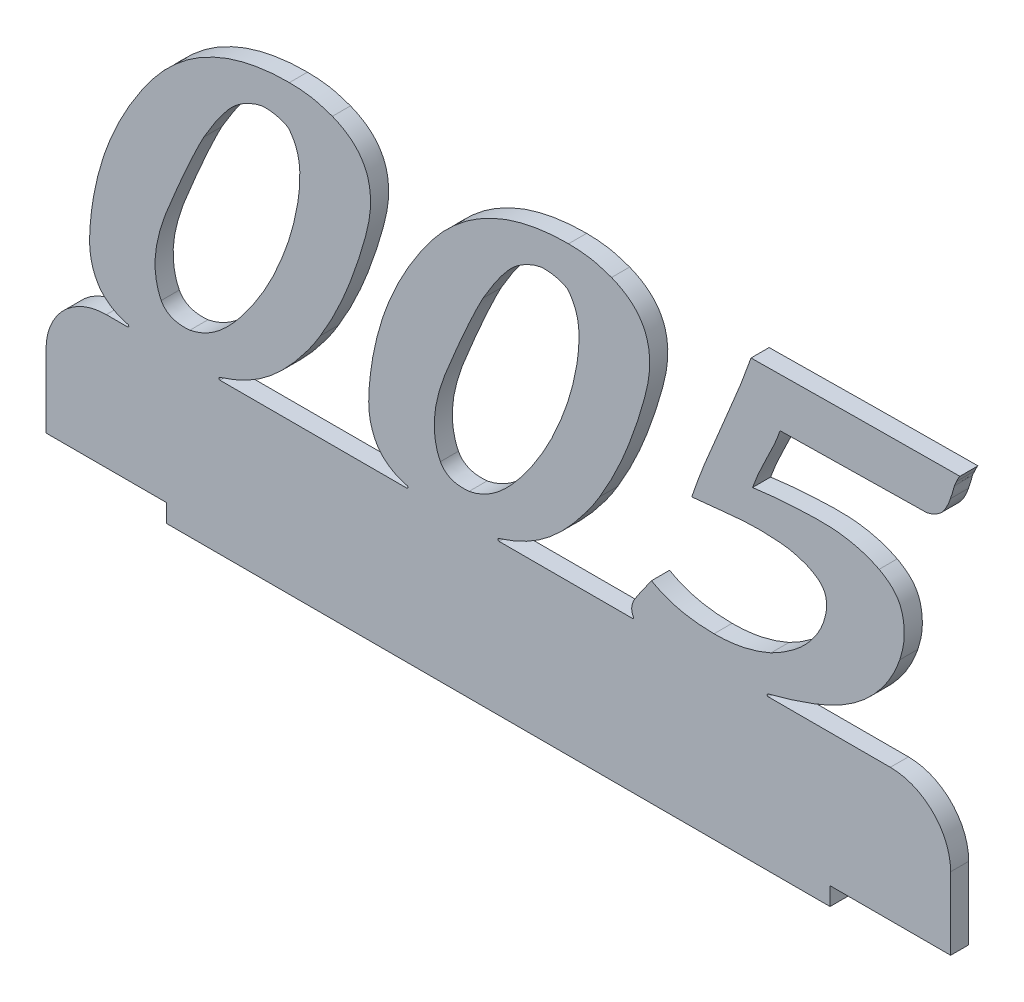
SolidWorks part; units mm, degrees
ref_plane "Front Plane" through (0, 0, 0) normal (0, 0, 1) x (1, 0, 0)
ref_plane "Top Plane" through (0, 0, 0) normal (0, 1, 0) x (1, 0, 0)
ref_plane "Right Plane" through (0, 0, 0) normal (1, 0, 0) x (0, 0, -1)
sketch "Sketch1" plane through (0, 0, 0) normal (0, 0, 1) x (1, 0, 0)
  line L0 (0, 20) -> (150, 20) construction
  line L1 (122.4075, 22) -> (150, 22)
  line L2 (0, 22) -> (0, 0)
  line L3 (0, 0) -> (20, 0)
  line L4 (150, 22) -> (150, 0)
  line L5 (0, 22) -> (15.1575, 22)
  line L6 (146.0617, 61.5809) -> (121.7068, 61.19)
  line L7 (27.4608, 22) -> (61.4437, 22)
  line L8 (73.747, 22) -> (97.6191, 22)
  line L9 (118.1123, 22) -> (122.4075, 22)
  line L11 (130, 0) -> (150, 0)
  line L13 (20, 0) -> (20, -3)
  line L14 (20, -3) -> (130, -3)
  line L15 (130, 0) -> (130, -3)
  spline S0 degree 3 poles (40.2173, 63.8874) (39.6161, 64.2969) (38.1508, 64.8031) (36.613, 64.9304) (35.7998, 64.8843) knots 0 0 0 0 0.469699 1 1 1 1
  spline S1 degree 3 poles (35.7998, 64.8843) (34.6551, 64.6436) (33.0371, 63.9661) (31.1487, 62.5885) (28.8408, 60.0104) (27.3071, 57.5589) (26.1634, 55.5801) knots 0 0 0 0 0.25259 0.375811 0.50377 1 1 1 1
  spline S2 degree 3 poles (26.1634, 55.5801) (25.7071, 54.7821) (25.1089, 53.4655) (24.2174, 51.6465) (23.5039, 50.0649) (22.7395, 48.3457) (21.939, 46.479) (21.0824, 44.4828) (20.2104, 42.3944) (19.4174, 40.2963) (18.7857, 38.2689) (18.3449, 36.3618) (18.102, 34.5688) (18.0547, 32.8895) (18.2564, 30.8638) (18.6759, 29.4401) (19.1071, 28.5864) knots 0 0 0 0 0.095871 0.150957 0.21155 0.277044 0.347448 0.42366 0.503899 0.583776 0.657815 0.725493 0.787949 0.846481 0.90051 1 1 1 1
  spline S3 degree 3 poles (19.1071, 28.5864) (19.4655, 27.8434) (20.965, 26.6361) (22.8779, 26.6195) (23.8569, 26.6904) knots 0 0 0 0 0.446154 1 1 1 1
  spline S4 degree 3 poles (23.8569, 26.6904) (25.3144, 26.9647) (27.471, 27.9832) (30.0033, 30.1509) (31.9538, 32.3081) (33.8206, 34.7936) (35.5821, 37.4676) (37.1726, 40.2941) (38.5671, 43.2504) (39.7652, 46.2674) (40.7568, 49.2794) (41.4755, 52.2679) (41.98, 55.1585) (42.1496, 57.8603) (41.9477, 60.8908) (41.0729, 62.8794) (40.2173, 63.8874) knots 0 0 0 0 0.099523 0.157976 0.224341 0.295662 0.367825 0.440561 0.514606 0.588508 0.65979 0.72866 0.796042 0.857776 0.911265 1 1 1 1
  spline S5 degree 3 poles (15.1575, 22) (14.4539, 22.1522) (13.2284, 22.4683) (11.5464, 23.0608) (10.24, 23.9106) (9.13, 24.9297) (8.3001, 26.207) (7.6946, 27.6785) (7.141, 30.0433) (7.2107, 31.963) (7.301, 33.2776) knots 0.420875 0.420875 0.420875 0.420875 0.501388 0.5623 0.61932 0.674488 0.729675 0.788153 0.851799 1 1 1 1
  spline S6 degree 3 poles (7.301, 33.2776) (7.4679, 35.5057) (7.9571, 38.8312) (9.0865, 43.168) (10.1493, 46.3774) (11.504, 49.5107) (13.042, 52.6166) (14.8497, 55.6597) (16.8568, 58.6269) (19.0543, 61.4162) (21.5286, 63.835) (24.1708, 65.9226) (27.0511, 67.57) (30.0866, 68.9179) (34.509, 70.1402) (37.9877, 70.5249) (40.3542, 70.4941) knots 0 0 0 0 0.122246 0.183381 0.245051 0.307032 0.370011 0.434579 0.500535 0.565958 0.62848 0.689454 0.749684 0.809559 0.870725 1 1 1 1
  spline S7 degree 3 poles (40.3542, 70.4941) (41.6144, 70.4837) (44.0572, 70.3402) (46.3974, 69.6303) (47.4886, 69.2236) knots 0 0 0 0 0.519885 1 1 1 1
  spline S8 degree 3 poles (47.4886, 69.2236) (48.7562, 68.7083) (50.5512, 67.715) (52.2906, 65.7321) (53.2001, 64.0586) (53.7154, 62.1537) (53.8807, 60.0366) (53.6876, 57.7059) (52.9382, 54.3664) (51.6596, 50.2) (49.3585, 43.8964) (47.1615, 39.4702) (45.4949, 36.7178) knots 0 0 0 0 0.111906 0.162582 0.212593 0.265416 0.321766 0.384451 0.454781 0.599581 0.738515 1 1 1 1
  spline S9 degree 3 poles (45.4949, 36.7178) (44.4034, 34.8605) (42.5331, 32.2901) (39.7838, 29.1671) (37.6151, 27.0978) (35.2326, 25.2902) (32.5529, 23.7944) (29.9294, 22.7279) (28.1886, 22.1966) (27.4608, 22) knots 0 0 0 0 0.25786 0.380114 0.498337 0.616577 0.737567 0.865048 0.955374 0.955374 0.955374 0.955374
  spline S10 degree 3 poles (86.5035, 63.8874) (85.9022, 64.2969) (84.437, 64.8031) (82.8992, 64.9304) (82.086, 64.8843) knots 0 0 0 0 0.469699 1 1 1 1
  spline S11 degree 3 poles (82.086, 64.8843) (80.9413, 64.6436) (79.3232, 63.9661) (77.4349, 62.5885) (75.127, 60.0104) (73.5933, 57.5589) (72.4496, 55.5801) knots 0 0 0 0 0.25259 0.375811 0.50377 1 1 1 1
  spline S12 degree 3 poles (72.4496, 55.5801) (71.9933, 54.7821) (71.3951, 53.4655) (70.5035, 51.6465) (69.7901, 50.0649) (69.0257, 48.3457) (68.2252, 46.479) (67.3686, 44.4828) (66.4965, 42.3944) (65.7036, 40.2963) (65.0719, 38.2689) (64.6311, 36.3618) (64.3882, 34.5688) (64.3409, 32.8895) (64.5426, 30.8638) (64.9621, 29.4401) (65.3933, 28.5864) knots 0 0 0 0 0.095871 0.150957 0.21155 0.277044 0.347448 0.42366 0.503899 0.583776 0.657815 0.725493 0.787949 0.846481 0.90051 1 1 1 1
  spline S13 degree 3 poles (65.3933, 28.5864) (65.7517, 27.8434) (67.2512, 26.6361) (69.1641, 26.6195) (70.1431, 26.6904) knots 0 0 0 0 0.446154 1 1 1 1
  spline S14 degree 3 poles (70.1431, 26.6904) (71.6006, 26.9647) (73.7572, 27.9832) (76.2895, 30.1509) (78.2399, 32.3081) (80.1067, 34.7936) (81.8683, 37.4676) (83.4587, 40.2941) (84.8532, 43.2504) (86.0514, 46.2674) (87.0429, 49.2794) (87.7616, 52.2679) (88.2662, 55.1585) (88.4358, 57.8603) (88.2339, 60.8908) (87.3591, 62.8794) (86.5035, 63.8874) knots 0 0 0 0 0.099523 0.157976 0.224341 0.295662 0.367825 0.440561 0.514606 0.588508 0.65979 0.72866 0.796042 0.857776 0.911265 1 1 1 1
  spline S15 degree 3 poles (61.4437, 22) (60.7401, 22.1522) (59.5146, 22.4683) (57.8325, 23.0608) (56.5261, 23.9106) (55.4162, 24.9297) (54.5863, 26.207) (53.9808, 27.6785) (53.4272, 30.0433) (53.4968, 31.963) (53.5872, 33.2776) knots 0.420875 0.420875 0.420875 0.420875 0.501388 0.5623 0.61932 0.674488 0.729675 0.788153 0.851799 1 1 1 1
  spline S16 degree 3 poles (53.5872, 33.2776) (53.7541, 35.5057) (54.2433, 38.8312) (55.3727, 43.168) (56.4355, 46.3774) (57.7901, 49.5107) (59.3281, 52.6166) (61.1359, 55.6597) (63.1429, 58.6269) (65.3405, 61.4162) (67.8147, 63.835) (70.457, 65.9226) (73.3372, 67.57) (76.3727, 68.9179) (80.7951, 70.1402) (84.2738, 70.5249) (86.6403, 70.4941) knots 0 0 0 0 0.122246 0.183381 0.245051 0.307032 0.370011 0.434579 0.500535 0.565958 0.62848 0.689454 0.749684 0.809559 0.870725 1 1 1 1
  spline S17 degree 3 poles (86.6403, 70.4941) (87.9006, 70.4837) (90.3434, 70.3402) (92.6836, 69.6303) (93.7748, 69.2236) knots 0 0 0 0 0.519885 1 1 1 1
  spline S18 degree 3 poles (93.7748, 69.2236) (95.0424, 68.7083) (96.8374, 67.715) (98.5767, 65.7321) (99.4862, 64.0586) (100.0015, 62.1537) (100.1668, 60.0366) (99.9737, 57.7059) (99.2243, 54.3664) (97.9458, 50.2) (95.6446, 43.8964) (93.4477, 39.4702) (91.7811, 36.7178) knots 0 0 0 0 0.111906 0.162582 0.212593 0.265416 0.321766 0.384451 0.454781 0.599581 0.738515 1 1 1 1
  spline S19 degree 3 poles (91.7811, 36.7178) (90.6896, 34.8605) (88.8193, 32.2901) (86.0699, 29.1671) (83.9012, 27.0978) (81.5188, 25.2902) (78.8391, 23.7944) (76.2156, 22.7279) (74.4747, 22.1966) (73.747, 22) knots 0 0 0 0 0.25786 0.380114 0.498337 0.616577 0.737567 0.865048 0.955374 0.955374 0.955374 0.955374
  spline S20 degree 3 poles (141.566, 38.2228) (141.0137, 36.678) (139.9546, 34.4359) (137.9556, 31.84) (136.2645, 30.0305) (134.2985, 28.4162) (132.0924, 26.9598) (129.6389, 25.6904) (126.984, 24.6338) (124.2649, 23.6931) (121.5779, 22.8735) (119.5304, 22.3356) (118.3856, 22.0633) (118.1123, 22) knots 0 0 0 0 0.120139 0.179294 0.238928 0.300824 0.364759 0.431861 0.502352 0.573447 0.64215 0.707652 0.72816 0.72816 0.72816 0.72816
  spline S22 degree 3 poles (97.6191, 22) (97.4954, 22.1475) (97.234, 22.5664) (97.0436, 23.393) (97.289, 24.4503) (97.9161, 25.4887) (98.6542, 26.5036) (99.4634, 27.6962) (100.0564, 28.4966) (100.4011, 28.9969) knots 0.046041 0.046041 0.046041 0.046041 0.11382 0.218197 0.338419 0.488512 0.646372 0.784334 1 1 1 1
  spline S23 degree 3 poles (100.4011, 28.9969) (101.8487, 28.1386) (105.2452, 26.8626) (108.8549, 26.5675) (110.7607, 26.5536) knots 0 0 0 0 0.467741 1 1 1 1
  spline S24 degree 3 poles (110.7607, 26.5536) (112.4058, 26.5477) (115.6541, 26.8471) (118.7459, 27.8831) (120.2017, 28.5278) knots 0 0 0 0 0.508189 1 1 1 1
  spline S25 degree 3 poles (120.2017, 28.5278) (121.2828, 29.0497) (122.7796, 29.9601) (124.6019, 31.3303) (125.7683, 32.3962) (126.7794, 33.5257) (127.9203, 35.0809) (128.5975, 36.3484) (128.8999, 37.2455) knots 0 0 0 0 0.285167 0.415664 0.541808 0.660346 0.775658 1 1 1 1
  spline S26 degree 3 poles (128.8999, 37.2455) (129.093, 37.8742) (129.3778, 38.784) (129.4746, 39.9904) (129.3831, 40.7711) (129.2296, 41.485) (128.8931, 42.1074) (128.464, 42.6652) (127.7015, 43.2903) (126.5851, 43.9455) (125.0588, 44.5167) (123.3581, 44.9646) (120.8148, 45.2278) (117.4487, 45.3564) (114.0636, 45.0968) (111.4586, 44.7972) (109.3673, 44.5794) (107.932, 44.4556) (107.0664, 44.3604) knots 0 0 0 0 0.071404 0.102518 0.130176 0.156356 0.180967 0.206089 0.232106 0.287157 0.345457 0.408083 0.477037 0.621747 0.772341 0.844017 0.905722 1 1 1 1
  spline S27 degree 3 poles (107.0664, 44.3604) (108.4749, 48.5751) (111.9316, 56.7932) (115.4526, 64.9833) (116.8983, 69.2236) knots 0 0 0 0 0.497975 1 1 1 1
  spline S28 degree 3 poles (116.8983, 69.2236) (122.658, 69.2919) (134.2034, 69.4098) (145.7486, 69.5659) (151.5348, 69.5559) knots 0 0 0 0 0.498878 1 1 1 1
  spline S29 degree 2 poles (151.5348, 69.5559) (151.2092, 69.1006) (151.007, 68.5786) knots 0 0 0 1 1 1
  spline S30 degree 3 poles (151.007, 68.5786) (150.889, 68.3432) (150.7753, 68.0701) (150.6125, 67.7813) (150.6161, 67.7185) knots 0 0 0 0 0.803037 1 1 1 1
  spline S31 degree 3 poles (150.6161, 67.7185) (150.4763, 67.2523) (150.3066, 66.5068) (150.052, 65.7865) (149.9515, 65.5293) knots 0 0 0 0 0.638073 1 1 1 1
  spline S32 degree 2 poles (149.9515, 65.5293) (149.5181, 64.126) (148.6223, 62.9687) knots 0 0 0 1 1 1
  spline S33 degree 2 poles (148.6223, 62.9687) (147.5516, 61.9027) (146.0617, 61.5809) knots 0 0 0 1 1 1
  spline S34 degree 3 poles (121.7068, 61.19) (121.1254, 59.3547) (119.386, 55.9744) (117.7605, 52.5396) (117.1524, 50.7522) knots 0 0 0 0 0.504223 1 1 1 1
  spline S35 degree 3 poles (117.1524, 50.7522) (118.8339, 50.9832) (121.4329, 51.2402) (125.0082, 51.4715) (127.8561, 51.5785) (130.6977, 51.5385) (134.2004, 51.0485) (136.6691, 50.2852) (138.1454, 49.5012) knots 0 0 0 0 0.238617 0.367155 0.503751 0.639403 0.766128 1 1 1 1
  spline S36 degree 3 poles (138.1454, 49.5012) (139.1323, 48.9531) (140.5422, 47.9787) (141.6889, 46.0996) (142.1409, 44.5972) (142.3213, 43.0307) (142.3074, 40.868) (141.9023, 39.268) (141.566, 38.2228) knots 0 0 0 0 0.263831 0.382077 0.502054 0.62342 0.745364 1 1 1 1
  dimension "D1" = 150
  dimension "D2" = 3
  dimension "D3" = 20
  dimension "D4" = 20
  dimension "D5" = 20
extrude "Boss-Extrude1" add sketch "Sketch1" along normal blind 3
fillet "Fillet1" radius 10 2 edges at (0, 22, 1.5) (150, 22, 1.5)
fillet "Fillet2" radius 0.2 6 edges at (97.6191, 22, 1.5) (61.4437, 22, 1.5) (15.1575, 22, 1.5) (27.4608, 22, 1.5) (73.747, 22, 1.5) (118.1123, 22, 1.5)
